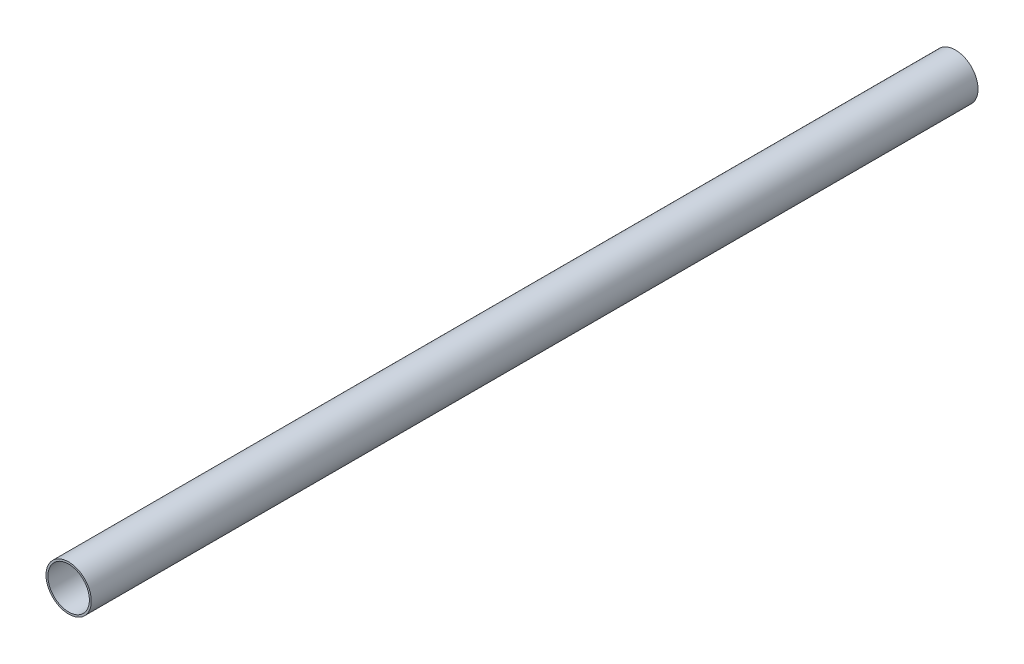
SolidWorks part; units mm, degrees
material "Karbon Fiber Boru "
ref_plane "Ön Düzlem" through (0, 0, 0) normal (0, 0, 1) x (1, 0, 0)
ref_plane "Üst Düzlem" through (0, 0, 0) normal (0, 1, 0) x (1, 0, 0)
ref_plane "Sağ Düzlem" through (0, 0, 0) normal (1, 0, 0) x (0, 0, -1)
sketch "Çizim1" plane through (0, 0, 0) normal (0, 0, 1) x (1, 0, 0)
  circle A0 centre (0, 0) radius 12
  circle A1 centre (0, 0) radius 11
  dimension "D1" = 24
  dimension "D2" = 22
extrude "Yükseklik-Ekstrüzyon1" add sketch "Çizim1" along normal blind 470
